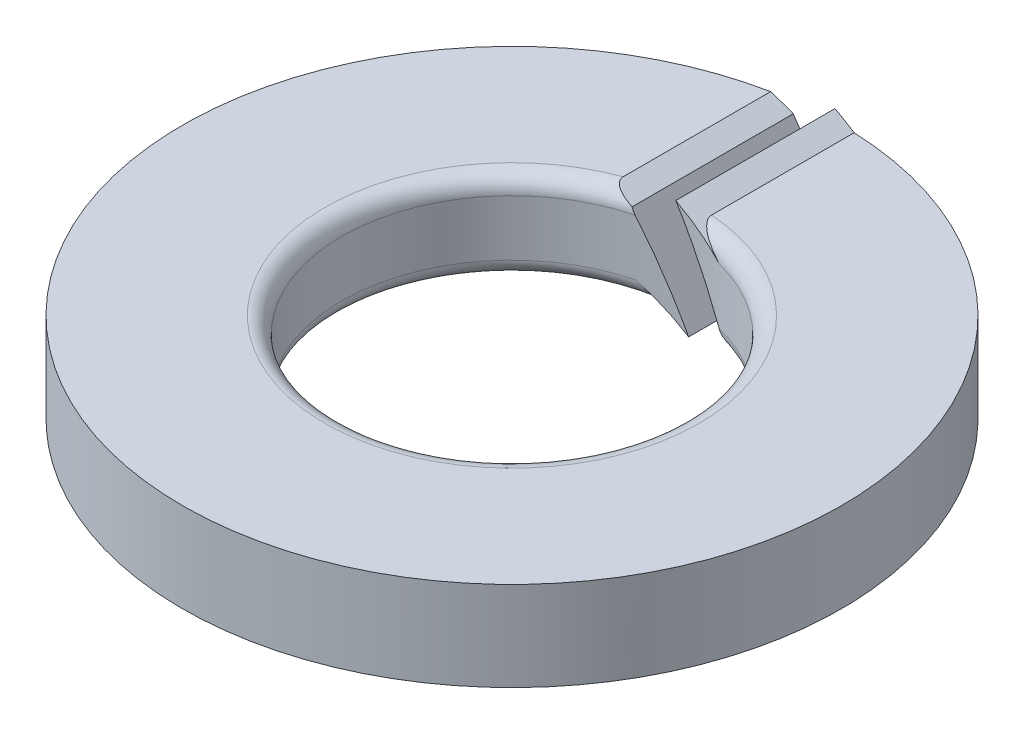
SolidWorks part; units mm, degrees
material "ASTM A36 Steel"
ref_plane "Front Plane" through (0, 0, 0) normal (0, 0, 1) x (1, 0, 0)
ref_plane "Top Plane" through (0, 0, 0) normal (0, 1, 0) x (1, 0, 0)
ref_plane "Right Plane" through (0, 0, 0) normal (1, 0, 0) x (0, 0, -1)
sketch "BodySke" plane through (0, 0, 0) normal (0, 0, 1) x (1, 0, 0)
  line L0 (0, 0) -> (0, 99.9596) construction
  line L1 (0, 0) -> (3.05, 0) construction
  line L3 (3.05, -10) -> (5.9, -10)
  line L4 (3.05, -10) -> (3.05, 10)
  line L5 (3.05, 10) -> (5.9, 10)
  line L6 (5.9, -10) -> (5.9, 10)
  line L7 (3.05, -0.8) -> (5.9, -0.8) construction
  line L8 (3.05, -0.8) -> (3.05, 0.8) construction
  line L9 (3.05, 0.8) -> (5.9, 0.8) construction
  line L10 (5.9, -0.8) -> (5.9, 0.8) construction
  dimension "Inner_dia" = 6.1
  dimension "Outer_dia" = 11.8
  dimension "D3" = 20
  dimension "Thickness" = 1.6
revolve "BaseBody" add sketch "BodySke" angle 360 about L0
sketch "Cut-ExtraSke" plane through (0, 0, 0) normal (0, 0, 1) x (1, 0, 0)
  line L1 (5.9, -0.8) -> (-5.9, -0.8)
  line L2 (5.9, -0.8) -> (5.9, -10)
  line L3 (5.9, -10) -> (-5.9, -10)
  line L4 (-5.9, -0.8) -> (-5.9, -10)
  line L5 (5.9, 0.8) -> (-5.9, 0.8)
  line L6 (5.9, 0.8) -> (5.9, 10)
  line L7 (5.9, 10) -> (-5.9, 10)
  line L8 (-5.9, 0.8) -> (-5.9, 10)
extrude "Cut-Extra" cut sketch "Cut-ExtraSke" along normal through all
sketch "ASke" plane through (0, 0, 0) normal (0, 0, 1) x (1, 0, 0)
  line L0 (0, -16.7192) -> (0, 28.802) construction
  line L1 (5.9, 0.8) -> (-5.9, 0.8) construction
  line L2 (0.1155, -1) -> (-0.9238, 0.8) construction
  line L4 (0.1155, -1) -> (-0.2309, -0.8)
  line L7 (-1.1547, 0.8) -> (-0.8083, 0.6)
  line L8 (-0.1155, 1) -> (0.9238, -0.8) construction
  line L9 (0.8083, -0.6) -> (1.1547, -0.8)
  line L10 (-5.9, 10) -> (5.9, 10)
  line L11 (-0.1155, 1) -> (0.2309, 0.8)
  line L12 (5.9, -0.8) -> (-5.9, -0.8) construction
  line L13 (5.9, 10) -> (5.9, 0.8)
  line L14 (5.9, 0.8) -> (0.2309, 0.8)
  line L15 (1.1547, -0.8) -> (5.9, -0.8)
  line L16 (5.9, -0.8) -> (5.9, -10)
  line L17 (5.9, -10) -> (-5.9, -10)
  line L18 (-5.9, -10) -> (-5.9, -0.8)
  line L19 (-5.9, -0.8) -> (-0.2309, -0.8)
  line L20 (0.1155, -1) -> (-0.8083, 0.6)
  line L21 (0.8083, -0.6) -> (-0.1155, 1)
  line L22 (-1.1547, 0.8) -> (-5.9, 0.8)
  line L23 (-5.9, 0.8) -> (-5.9, 10)
  line L24 (-5.9, 10) -> (-5.9, 0.8) construction
  line L25 (-5.9, -0.8) -> (-5.9, -10) construction
  line L26 (3.05, 10) -> (5.9, 10) construction
  line L27 (3.05, -10) -> (5.9, -10) construction
  point P11 (0, -0.8)
  point P12 (0, 0.8)
  dimension "Angle" = 30
  dimension "Side_angle" = 60
  dimension "Offset" = 0.2
  dimension "D4" = 0.2
  dimension "D5" = 0.2
  dimension "D6" = 0.2
extrude "Type-A" cut sketch "ASke" against normal through all
sketch "BSke" plane through (0, 0, 0) normal (0, 0, 1) x (1, 0, 0)
  line L0 (0, 0) -> (0, 31.0126) construction
  line L1 (0, 0) -> (0, 99.9596) construction
  line L2 (0, -0.8) -> (-0.9238, 0.8)
  line L3 (5.9, 0.8) -> (-5.9, 0.8) construction
  line L4 (0, 0.8) -> (0.9238, -0.8)
  line L5 (-5.9, -0.8) -> (5.9, -0.8) construction
  line L6 (-3.05, -0.8) -> (3.05, -0.8) construction
  line L7 (0, -0.8) -> (-5.9, -0.8)
  line L8 (-5.9, -0.8) -> (-5.9, -10)
  line L9 (-5.9, -10) -> (5.9, -10)
  line L10 (5.9, -10) -> (5.9, -0.8)
  line L11 (5.9, -0.8) -> (0.9238, -0.8)
  line L12 (0, 0.8) -> (5.9, 0.8)
  line L13 (5.9, 0.8) -> (5.9, 10)
  line L14 (5.9, 10) -> (-5.9, 10)
  line L15 (-5.9, 10) -> (-5.9, 0.8)
  line L16 (-5.9, 0.8) -> (-0.9238, 0.8)
  line L17 (-5.9, 0.8) -> (-5.9, -0.8) construction
  dimension "Angle" = 30
extrude "Type-B" [suppressed] cut sketch "BSke" against normal through all
fillet "Fillet1" radius 0.3 2 edges at (-0.4746, -0.8, 3.0128) (0.4746, 0.8, 3.0128)
equation "\"D4@ASke\" = \"Offset@ASke\""
equation "\"D5@ASke\" = \"Offset@ASke\""
equation "\"D6@ASke\" = \"Offset@ASke\""
